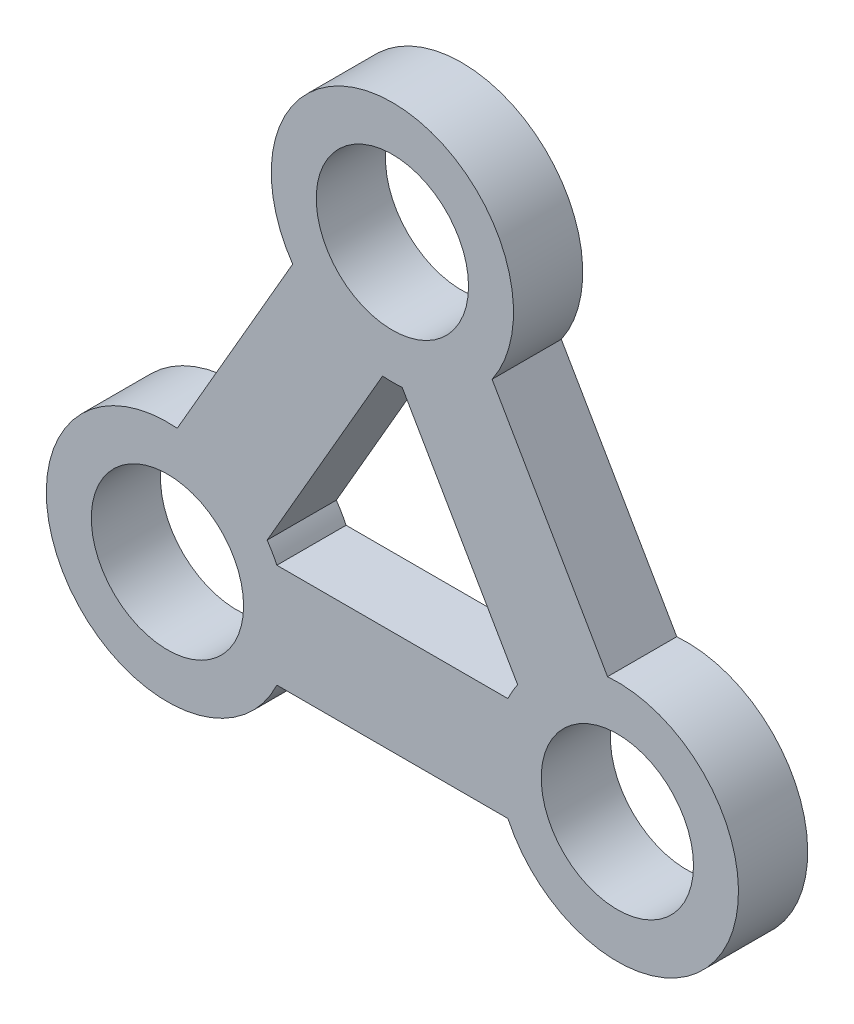
SolidWorks part; units mm, degrees
ref_plane "Front Plane" through (0, 0, 0) normal (0, 0, 1) x (1, 0, 0)
ref_plane "Top Plane" through (0, 0, 0) normal (0, 1, 0) x (1, 0, 0)
ref_plane "Right Plane" through (0, 0, 0) normal (1, 0, 0) x (0, 0, -1)
sketch "Sketch1" plane through (0, 0, 0) normal (0, 0, 1) x (1, 0, 0)
  line L0 (-65, 0) -> (65, 0) construction
  line L1 (-57.6618, 112.5) -> (57.6618, 112.5) construction
  line L2 (0, -51.9346) -> (0, 112.5) construction
  line L3 (-33.3772, -15) -> (33.3772, -15)
  line L4 (-65, 0) -> (0, 112.5) construction
  line L5 (0, 112.5) -> (65, 0) construction
  line L6 (-62.1678, 34.8852) -> (-28.8081, 92.6231)
  line L7 (28.8081, 92.6231) -> (62.1678, 34.8852)
  line L8 (0, 0) -> (0, 112.5)
  line L9 (-33.3772, 15) -> (33.3772, 15)
  line L10 (-36.1919, 19.8769) -> (-2.8322, 77.6148)
  line L11 (2.8322, 77.6148) -> (36.1919, 19.8769)
  circle A0 centre (0, 112.5) radius 22
  circle A1 centre (65, 0) radius 22
  circle A2 centre (-65, 0) radius 22
  arc A3 (28.8081, 92.6231) -> (-28.8081, 92.6231) centre (0, 112.5) ccw
  arc A4 (33.3772, -15) -> (62.1678, 34.8852) centre (65, 0) ccw
  arc A5 (-62.1678, 34.8852) -> (-33.3772, -15) centre (-65, 0) ccw
  arc A6 (-33.3772, 15) -> (-36.1919, 19.8769) centre (-65, 0) ccw
  arc A7 (36.1919, 19.8769) -> (33.3772, 15) centre (65, 0) ccw
  arc A8 (-2.8322, 77.6148) -> (2.8322, 77.6148) centre (0, 112.5) ccw
  point P4 (0, 0)
  point P8 (0, 112.5)
  dimension "D3" = 44
  dimension "D4" = 44
  dimension "D5" = 44
  dimension "D6" = 70
  dimension "D7" = 70
  dimension "D8" = 70
  dimension "D9" = 15
  dimension "D1" = 130
  dimension "D2" = 112.5
  dimension "D10" = 15
  dimension "D11" = 15
  dimension "D12" = 30
  dimension "D13" = 30
  dimension "D14" = 30
extrude "Boss-Extrude1" add sketch "Sketch1" along normal blind 20 contours L7 A4 L3 A5 L6 A3 | A2 | L11 A7 L9 A6 L10 A8 | A0 | A1
